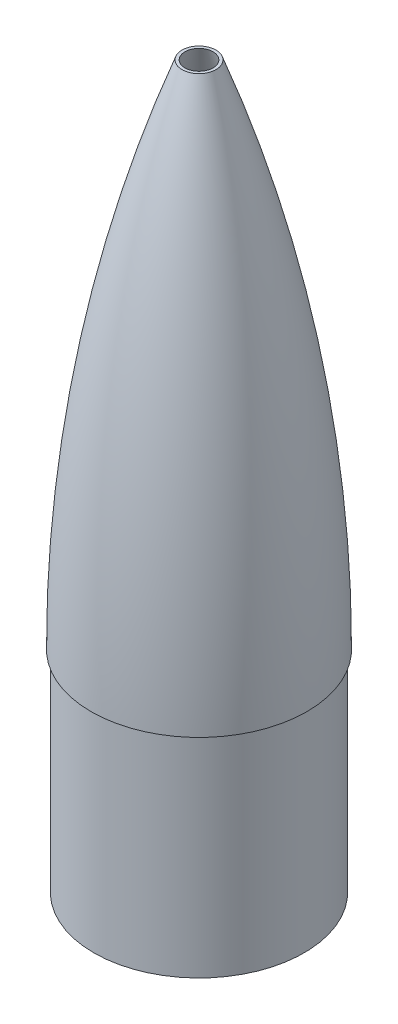
SolidWorks part; units mm, degrees
other "Markup1"
sketch "Sketch4" plane through (78.16, -154.2442, 78.16) normal (0.9651, -0.1718, 0.1975) x (-0.1686, -0.9851, -0.0334)
material "Thornel Mat VMA"
ref_plane "Front Plane" through (0, 0, 0) normal (0, 0, 1) x (1, 0, 0)
ref_plane "Top Plane" through (0, 0, 0) normal (0, 1, 0) x (1, 0, 0)
ref_plane "Right Plane" through (0, 0, 0) normal (1, 0, 0) x (0, 0, -1)
sketch "Sketch1" plane through (0, 0, 0) normal (0, 0, 1) x (1, 0, 0)
  line L3 (0, 0) -> (0, 398.8705) construction
  line L6 (0, 400) -> (0, 401.8534)
  line L8 (78.2, 0) -> (76.2, 0)
  line L9 (0, 400) -> (0, 396.4892)
  line L10 (76.2, 0) -> (-993.4203, 0) construction
  line L11 (0, 411.0234) -> (0, 614.1078) construction
  arc A0 (76.2, 0) -> (0, 396.4892) centre (-993.4203, 0) ccw
  arc A1 (78.2, 0) -> (0, 401.8534) centre (-993.4203, 0) ccw
  circle A2 centre (-993.4203, 0) radius 1069.6203 construction
  circle A3 centre (-993.4203, 0) radius 1071.6203 construction
  point P11 (0, 400)
  dimension "D1" = 400
  dimension "D2" = 3.5108
  dimension "D3" = 2
  dimension "D4" = 76.2
revolve "Revolve3" add sketch "Sketch1" angle 360 about L6
sketch "Sketch2" plane through (0, 0, 0) normal (0, 1, 0) x (1, 0, 0)
  circle A3 centre (0, 0) radius 76.2 construction
  circle A4 centre (0, 0) radius 76.2
  circle A5 centre (0, 0) radius 74.2
  dimension "D1" = 2
extrude "Boss-Extrude1" add sketch "Sketch2" against normal blind 152.4 and the other way blind 10
ref_plane "Plane2" through (0, 400, 0) normal (0, -1, 0) x (-1, 0, 0)
ref_plane "Plane4" through (0, 370, 0) normal (0, -1, 0) x (-1, 0, 0)
sketch "Sketch6" plane through (0, 370, 0) normal (0, -1, 0) x (-1, 0, 0)
  circle A0 centre (0, 0) radius 45.0274
extrude "Cut-Extrude1" cut sketch "Sketch6" against normal blind 40
ref_plane "Plane3" through (0, -6.4, 0) normal (0, -1, 0) x (-1, 0, 0)
sketch "Sketch5" plane through (0, -6.4, 0) normal (0, -1, 0) x (-1, 0, 0)
  circle A0 centre (0, 0) radius 73.2
  circle A1 centre (0, 0) radius 73.2
